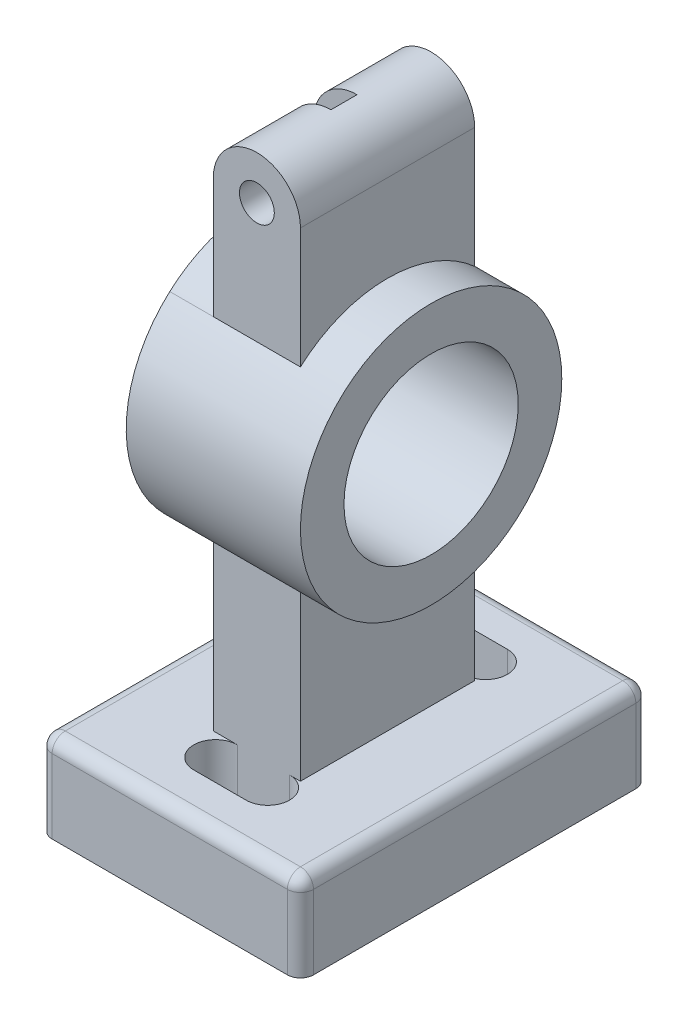
SolidWorks part; units mm, degrees
ref_plane "Front Plane" through (0, 0, 0) normal (0, 0, 1) x (1, 0, 0)
ref_plane "Top Plane" through (0, 0, 0) normal (0, 1, 0) x (1, 0, 0)
ref_plane "Right Plane" through (0, 0, 0) normal (1, 0, 0) x (0, 0, -1)
sketch "Sketch1" plane through (0, 0, 0) normal (0, 1, 0) x (1, 0, 0)
  line L0 (-0.2245, -1.25) -> (0.3755, -1.25) construction
  line L1 (-1.35, 2) -> (1.35, 2)
  line L2 (-1.5, 1.85) -> (-1.5, -1.85)
  line L3 (-1.35, -2) -> (1.35, -2)
  line L4 (1.5, 1.85) -> (1.5, -1.85)
  line L5 (-1.5, 2) -> (1.5, -2) construction
  line L6 (-1.5, -2) -> (1.5, 2) construction
  line L9 (-0.2245, 1.25) -> (0.3755, 1.25) construction
  line L10 (-0.2245, 1.5) -> (0.3755, 1.5)
  line L11 (-0.2245, 1) -> (0.3755, 1)
  line L13 (-0.2245, -1.5) -> (0.3755, -1.5)
  line L14 (-0.2245, -1) -> (0.3755, -1)
  arc A0 (1.35, -2) -> (1.5, -1.85) centre (1.35, -1.85) ccw
  arc A1 (1.35, 2) -> (1.5, 1.85) centre (1.35, 1.85) cw
  arc A2 (-1.35, 2) -> (-1.5, 1.85) centre (-1.35, 1.85) ccw
  arc A3 (-1.5, -1.85) -> (-1.35, -2) centre (-1.35, -1.85) ccw
  arc A6 (-0.2245, 1.5) -> (-0.2245, 1) centre (-0.2245, 1.25) ccw
  arc A7 (0.3755, 1) -> (0.3755, 1.5) centre (0.3755, 1.25) ccw
  arc A8 (-0.2245, -1.5) -> (-0.2245, -1) centre (-0.2245, -1.25) cw
  arc A9 (0.3755, -1) -> (0.3755, -1.5) centre (0.3755, -1.25) cw
  point P0 (0, 0)
  point P20 (0.0755, -1.25)
  point P27 (0.0755, 1.25)
  dimension "D3" = 0.15
  dimension "D4" = 0.25
  dimension "D1" = 3
  dimension "D2" = 4
  dimension "D5" = 0.75
  dimension "D6" = 0.6
extrude "Boss-Extrude1" add sketch "Sketch1" along normal blind 1
fillet "Fillet1" radius 0.15 8 edges at (-1.4561, 1, 1.9561) (-1.5, 1, 0) (-1.4561, 1, -1.9561) (0, 1, -2) (1.4561, 1, -1.9561) (1.5, 1, 0) (1.4561, 1, 1.9561) (0, 1, 2)
sketch "Sketch2" plane through (0, 0, 0) normal (0, 0, 1) x (1, 0, 0)
  line L0 (-1.35, 1) -> (1.35, 1) construction
  line L1 (-0.5, 1) -> (0.5, 1)
  line L2 (-0.5, 1) -> (-0.5, 6.5)
  line L4 (0.5, 1) -> (0.5, 6.5)
  arc A0 (0.5, 6.5) -> (-0.5, 6.5) centre (0, 6.5) ccw
  circle A1 centre (0, 6.5) radius 0.2
  dimension "D1" = 5.5
  dimension "D2" = 1
  dimension "D3" = 0.5
extrude "Boss-Extrude2" add sketch "Sketch2" along normal mid plane 2
sketch "Sketch3" plane through (0, 0, 0) normal (1, 0, 0) x (0, 0, -1)
  line L0 (-1, 1) -> (1, 1) construction
  circle A0 centre (0, 4) radius 1
  circle A1 centre (0, 4) radius 1.5
  dimension "D2" = 3
  dimension "D3" = 2
  dimension "D1" = 3
extrude "Boss-Extrude3" add sketch "Sketch3" along normal mid plane 2
sketch "Sketch4" plane through (-0.5, 0, 0) normal (-1, 0, 0) x (0, 0, 1)
  circle A2 centre (0, 4) radius 1
  circle A3 centre (0, 4) radius 1
  dimension "D1" = 0
extrude "Cut-Extrude1" cut sketch "Sketch4" against normal through all
sketch "Sketch5" plane through (0, 0, 0) normal (1, 0, 0) x (0, 0, -1)
  line L1 (0.15, 4.9887) -> (0.15, 7)
  line L2 (-0.15, 4.9887) -> (-0.15, 7)
  line L8 (0.15, 7) -> (-0.15, 7)
  arc A4 (0.15, 4.9887) -> (-0.15, 4.9887) centre (0, 4) ccw
extrude "Cut-Extrude3" cut sketch "Sketch5" against normal blind 2
